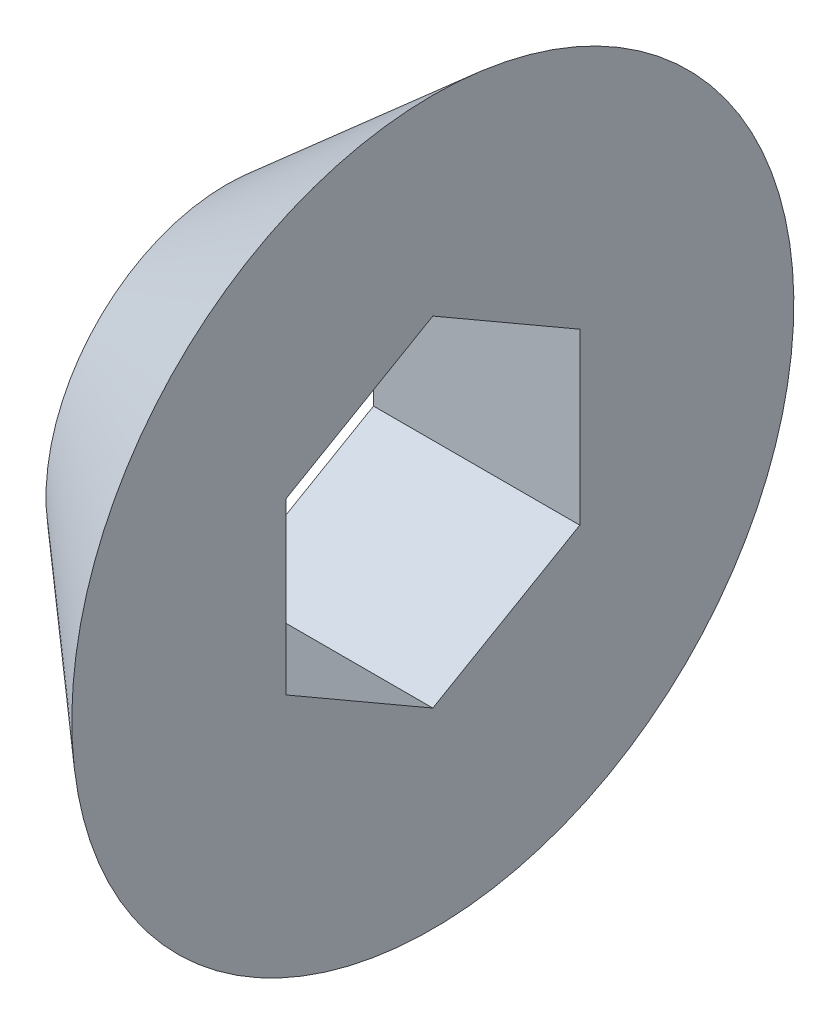
SolidWorks part; units mm, degrees
material "PLA"
ref_plane "Plan de face" through (0, 0, 0) normal (0, 0, 1) x (1, 0, 0)
ref_plane "Plan de dessus" through (0, 0, 0) normal (0, 1, 0) x (1, 0, 0)
ref_plane "Plan de droite" through (0, 0, 0) normal (1, 0, 0) x (0, 0, -1)
sketch "Sketch1" plane through (0, 0, 0) normal (0, 0, 1) x (1, 0, 0)
  line L0 (0, 0) -> (-4, 0)
  line L1 (-4, 0) -> (-4, 3.5)
  line L2 (-4, 3.5) -> (0, 7)
  line L3 (0, 7) -> (0, 0)
  dimension "D1" = 7
  dimension "D2" = 3.5
  dimension "D3" = 4
revolve "Revolve1" add sketch "Sketch1" angle 360 about L0
sketch "Sketch2" plane through (-4, 0, 0) normal (-1, 0, 0) x (0, 0, 1)
  line L1 (0, 3.2909) -> (-2.85, 1.6454)
  line L2 (-2.85, 1.6454) -> (-2.85, -1.6454)
  line L3 (-2.85, -1.6454) -> (0, -3.2909)
  line L4 (0, -3.2909) -> (2.85, -1.6454)
  line L5 (2.85, -1.6454) -> (2.85, 1.6454)
  line L6 (2.85, 1.6454) -> (0, 3.2909)
  circle A0 centre (0, 0) radius 2.85 construction
  dimension "D1" = 5.7
extrude "Cut-Extrude1" cut sketch "Sketch2" against normal through all
